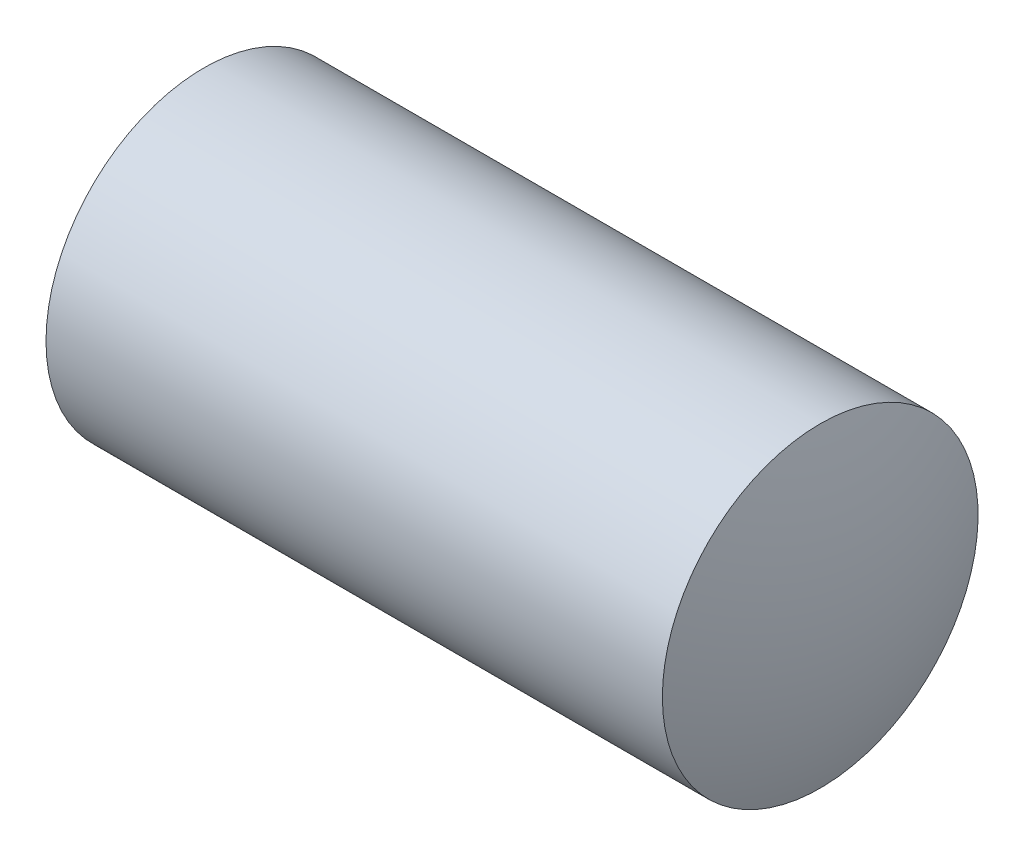
SolidWorks part; units mm, degrees
revolve "BaseBody" add sketch "BodySke" angle 360 about L5
sketch "BodySke" plane through (0, 0, 0) normal (0, 0, 1) x (1, 0, 0)
  line L0 (0, 0) -> (0, 10.352)
  line L1 (0, 10.352) -> (0.9515, 12)
  line L2 (0.9515, 12) -> (47.8119, 12)
  line L3 (48.3857, 15.875) -> (48.3857, -3.175) construction
  line L4 (50, 0) -> (0, 0)
  line L5 (-12.7, 0) -> (88.9, 0) construction
  line L8 (0, -10.352) -> (0.9515, -12) construction
  line L9 (3, 15.875) -> (3, -3.175) construction
  arc A0 (50, 0) -> (47.8119, 12) centre (16, 0) ccw
  dimension "Oval_rad" = 34
  dimension "Diameter" = 24
  dimension "Drive_ch_ang" = 60
  dimension "Minor_dia" = 20.704
  dimension "Advance" = 3
  dimension "Length" = 50
  dimension "Thread_len" = 47.4343
cosmetic thread "ThreadCosmetic" [suppressed] parameters "Thread_minor"=20.704
ref_plane "Plane1" through (0, 0, 0) normal (0, 0, 1) x (1, 0, 0)
ref_plane "Plane2" through (0, 0, 0) normal (0, 1, 0) x (1, 0, 0)
ref_plane "Plane3" through (0, 0, 0) normal (1, 0, 0) x (0, 0, -1)
sketch "Sketch2" plane through (0, 0, 0) normal (-1, 0, 0) x (0, 0, 1)
  line L0 (3.4641, 6) -> (-3.4641, 6)
  line L1 (-3.4641, 6) -> (-6.9282, 0)
  line L2 (3.4641, 6) -> (6.9282, 0)
  line L3 (3.4641, -6) -> (6.9282, 0)
  line L4 (3.4641, -6) -> (-3.4641, -6)
  line L5 (-3.4641, -6) -> (-6.9282, 0)
  dimension "Hex_size" = 12
  dimension "D2" = 6
  dimension "D3" = 6
extrude "Hex" cut sketch "Sketch2" against normal blind 15
sketch "ThdSchSke" plane through (0, 0, 0) normal (0, 0, 1) x (1, 0, 0)
  line L0 (0.9515, -10.352) -> (-0.2025, -12)
  line L1 (0.9515, -10.352) -> (2.1054, -12)
  line L2 (2.1054, -12) -> (2.1054, -15)
  line L3 (-3.175, 0) -> (5.1513, 0) construction
  line L5 (2.1054, -15) -> (-0.2025, -15)
  line L6 (-0.2025, -15) -> (-0.2025, -12)
  line L8 (0.9515, 12) -> (0.9515, -12) construction
  dimension "Thread_minor" = 20.704
  dimension "Diameter" = 24
revolve "ThreadSchematic" [suppressed] cut sketch "ThdSchSke" angle 360 about L3
pattern_linear "ThdSchPat" [suppressed]
equation "\"D2@Sketch2\" = \"Hex_size@Sketch2\" / 2"
equation "\"D3@Sketch2\" = \"Hex_size@Sketch2\" / 2"
equation "\"Thread_minor@ThreadCosmetic\" = \"Minor_dia@BodySke\""
equation "\"Thread_minor@ThdSchSke\" = \"Thread_minor@ThreadCosmetic\""
equation "\"Diameter@ThdSchSke\" = \"Diameter@BodySke\""
equation "\"Overcut@ThdSchSke\" = \"Diameter@BodySke\" * 1.25"
equation "\"Thread_len@BodySke\" = \"Length@BodySke\" -  ( ( ( \"Diameter@BodySke\" - \"Minor_dia@BodySke\" ) * 0.5 ) / tan( \"Drive_ch_ang@BodySke\" * 0.017453292 ) )"
equation "\"Thread_len@BodySke\" = \"Thread_len@BodySke\" - \"Oval_rad@BodySke\" + sqr(\"Oval_rad@BodySke\" * \"Oval_rad@BodySke\" - (\"Minor_dia@BodySke\" / 2) * (\"Minor_dia@BodySke\" / 2))"
equation "\"Num_threads@ThdSchPat\" = int( \"Thread_len@BodySke\" / \"Advance@BodySke\" + 0.999 )  + 1"
equation "\"Advance@ThdSchPat\" = \"Thread_len@BodySke\" /  (\"Num_threads@ThdSchPat\" - 1) 'relax it"
